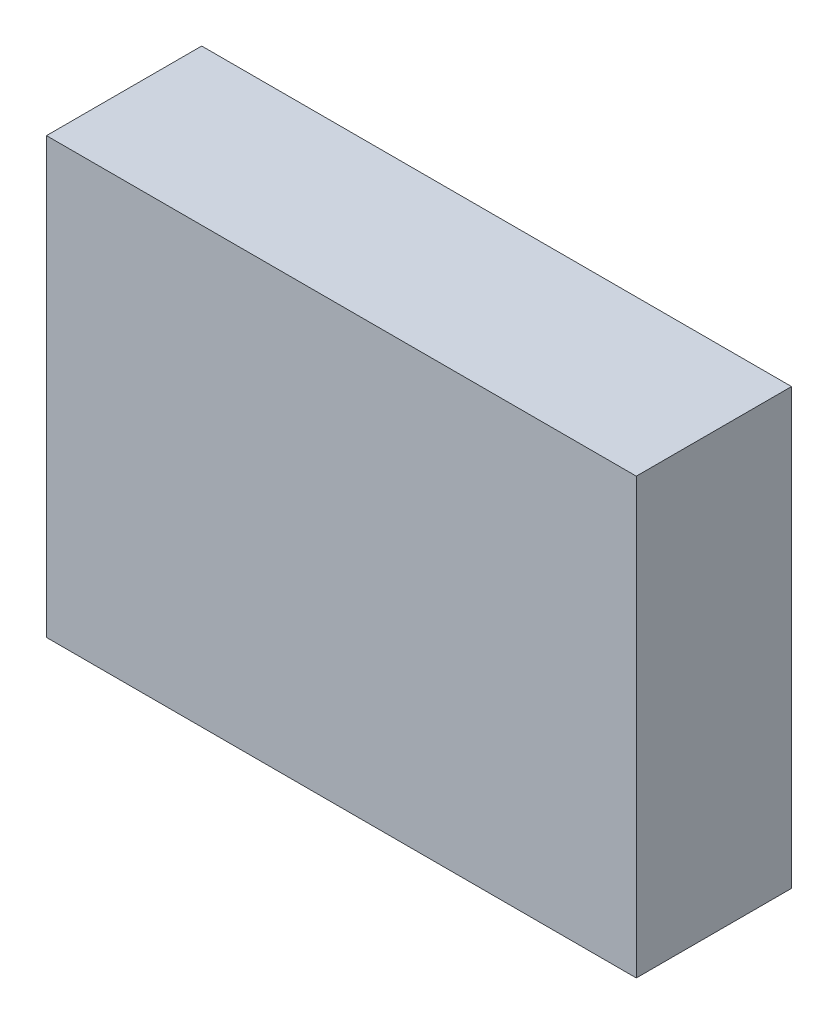
SolidWorks part; units mm, degrees
ref_plane "Front Plane" through (0, 0, 0) normal (0, 0, 1) x (1, 0, 0)
ref_plane "Top Plane" through (0, 0, 0) normal (0, 1, 0) x (1, 0, 0)
ref_plane "Right Plane" through (0, 0, 0) normal (1, 0, 0) x (0, 0, -1)
sketch "Sketch1" plane through (0, 0, 0) normal (0, 0, 1) x (1, 0, 0)
  line L1 (-95, -70) -> (95, -70)
  line L2 (-95, -70) -> (-95, 70)
  line L3 (-95, 70) -> (95, 70)
  line L4 (95, -70) -> (95, 70)
  line L5 (-95, -70) -> (95, 70) construction
  line L6 (-95, 70) -> (95, -70) construction
  point P0 (0, 0)
extrude "Boss-Extrude1" add sketch "Sketch1" along normal blind 50
sketch "Sketch2" plane through (0, -70, 0) normal (0, -1, 0) x (-1, 0, 0)
  line L0 (0, -50) -> (0, 0) construction
  line L1 (95, -50) -> (-95, -50) construction
  line L2 (95, 0) -> (-95, 0) construction
  line L3 (-10, -50) -> (10, -50)
  line L4 (45, 0) -> (-45, 0)
  line L5 (10, -50) -> (10, -35)
  line L6 (10, -35) -> (45, 0)
  line L7 (-10, -35) -> (-45, 0)
  line L8 (-10, -50) -> (-10, -35)
  dimension "D1" = 15
  dimension "D2" = 45
sketch "Sketch3" plane through (0, 0, 50) normal (0, 0, 1) x (1, 0, 0)
  line L0 (-95, 0) -> (95, 0) construction
  line L1 (-95, 70) -> (-95, -70) construction
  line L2 (95, -70) -> (95, 70) construction
ref_plane "Plane1" through (0, 0, 0) normal (0, -1, 0) x (1, 0, 0)
sketch "Sketch4" plane through (0, 0, 50) normal (0, 0, 1) x (1, 0, 0)
  line L0 (-95, 0) -> (95, 0) construction
  line L1 (-95, 70) -> (-95, -70) construction
  line L2 (95, -70) -> (95, 70) construction
